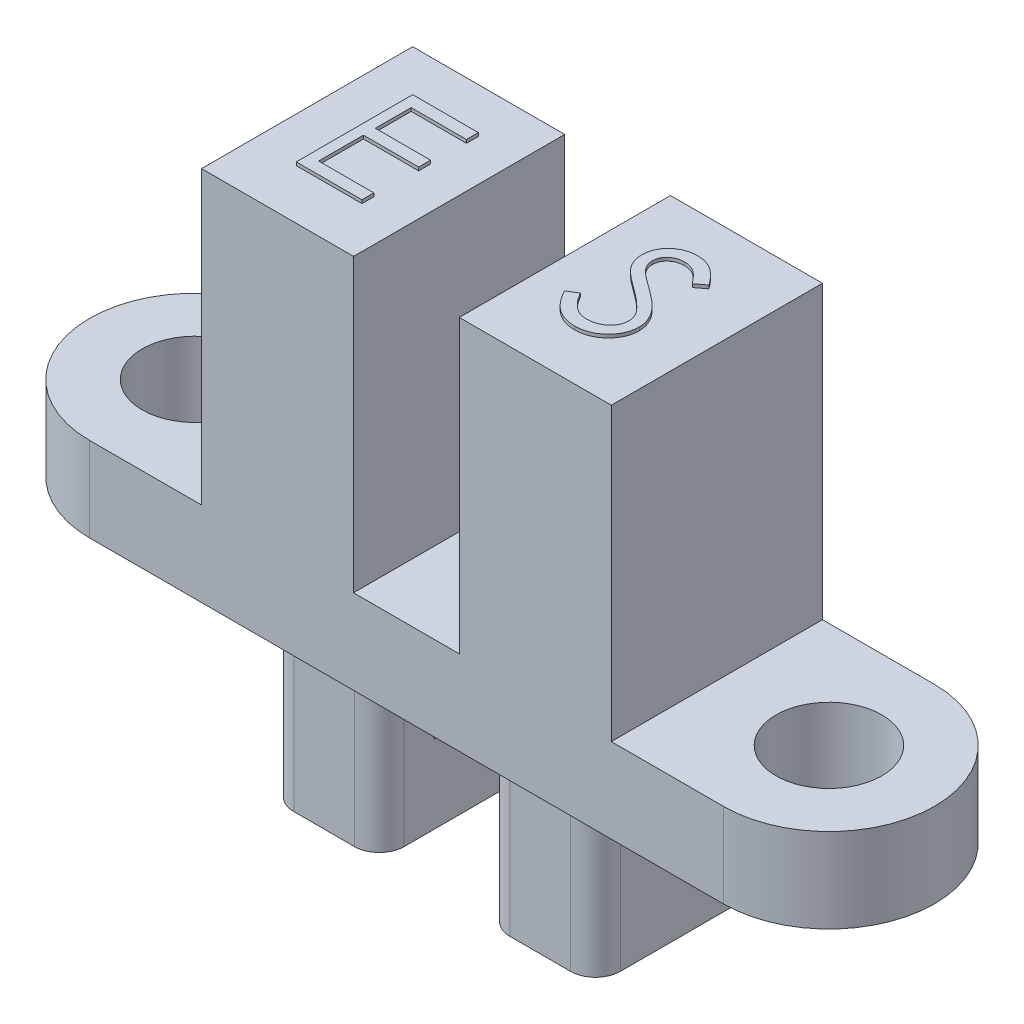
SolidWorks part; units mm, degrees
ref_plane "Front Plane" through (0, 0, 0) normal (0, 0, 1) x (1, 0, 0)
ref_plane "Top Plane" through (0, 0, 0) normal (0, 1, 0) x (1, 0, 0)
ref_plane "Right Plane" through (0, 0, 0) normal (1, 0, 0) x (0, 0, -1)
sketch "Sketch1" plane through (0, 0, 0) normal (0, 1, 0) x (1, 0, 0)
  line L0 (0, 6.2271) -> (0, -7.4076) construction
  line L1 (-9.2668, 0) -> (10.8605, 0) construction
  line L2 (9.53, 3.1745) -> (-9.53, 3.1745)
  line L3 (9.53, -3.1745) -> (-9.53, -3.1745)
  circle A0 centre (-9.53, 0) radius 1.59
  arc A1 (-9.53, 3.1745) -> (-9.53, -3.1745) centre (-9.53, 0) ccw
  circle A2 centre (9.53, 0) radius 1.59
  arc A3 (9.53, 3.1745) -> (9.53, -3.1745) centre (9.53, 0) cw
  point P8 (0, -3.1745)
  point P12 (0, 0)
  point P16 (0, 3.1745)
  dimension "D1" = 3.18
  dimension "D2" = 9.53
  dimension "D3" = 6.349
extrude "Boss-Extrude1" add sketch "Sketch1" along normal blind 2.54
sketch "Sketch2" plane through (0, 2.54, 0) normal (0, 1, 0) x (1, 0, 0)
  line L0 (0, 3.1745) -> (0, -3.1745) construction
  line L1 (9.53, 3.1745) -> (-9.53, 3.1745) construction
  line L2 (-9.53, -3.1745) -> (9.53, -3.1745) construction
  line L3 (-1.59, 3.1745) -> (-1.59, -3.1745)
  line L4 (-6.16, 3.1745) -> (-6.16, -3.1745)
  line L5 (-6.16, 3.1745) -> (-1.59, 3.1745)
  line L6 (-6.16, -3.1745) -> (-1.59, -3.1745)
  line L7 (6.16, 3.1745) -> (6.16, -3.1745)
  line L8 (6.16, 3.1745) -> (1.59, 3.1745)
  line L9 (1.59, 3.1745) -> (1.59, -3.1745)
  line L10 (6.16, -3.1745) -> (1.59, -3.1745)
  dimension "D1" = 3.18
  dimension "D2" = 6.16
extrude "Boss-Extrude2" add sketch "Sketch2" along normal blind 8.76
sketch "Sketch3" plane through (0, 0, 0) normal (0, -1, 0) x (1, 0, 0)
  line L0 (0, 3.1745) -> (0, -3.1745) construction
  line L1 (-9.53, 3.1745) -> (9.53, 3.1745) construction
  line L2 (9.53, -3.1745) -> (-9.53, -3.1745) construction
  line L3 (-5.2064, 0) -> (6.1252, 0) construction
  line L4 (4.91, 2.4) -> (1.59, 2.4)
  line L5 (-4.91, -2.4) -> (-1.59, -2.4)
  line L6 (-4.91, -2.4) -> (-4.91, 2.4)
  line L7 (-4.91, 2.4) -> (-1.59, 2.4)
  line L8 (-1.59, -2.4) -> (-1.59, 2.4)
  line L9 (-4.91, -2.4) -> (-1.59, 2.4) construction
  line L10 (-4.91, 2.4) -> (-1.59, -2.4) construction
  line L11 (1.59, -2.4) -> (1.59, 2.4)
  line L12 (4.91, -2.4) -> (1.59, -2.4)
  line L13 (4.91, -2.4) -> (4.91, 2.4)
  point P7 (-3.25, 0)
  dimension "D1" = 3.18
  dimension "D2" = 4.8
  dimension "D3" = 3.32
extrude "Boss-Extrude3" add sketch "Sketch3" along normal blind 4.83
sketch "Sketch6" plane through (0, 0, 0) normal (0, 0, 1) x (1, 0, 0)
  line L0 (1.59, -4.83) -> (1.59, 0) construction
  line L1 (-1.59, -4.83) -> (-1.59, 0) construction
  line L2 (9.53, 0) -> (-9.53, 0) construction
  line L3 (-1.59, -2.5) -> (-1.59, 0)
  line L4 (-1.59, 0) -> (1.59, 0)
  line L5 (1.59, 0) -> (1.59, -2.5)
  arc A0 (1.59, -2.5) -> (-1.59, -2.5) centre (0, -2.5) ccw
  dimension "D1" = 2.5
extrude "Boss-Extrude5" add sketch "Sketch6" along normal blind 0.75 and the other way blind 0.75
sketch "Sketch7" plane through (0, 0, 0) normal (0, -1, 0) x (1, 0, 0)
  line L0 (4.91, 2.4) -> (1.59, 2.4) construction
  line L1 (5.41, -2.9) -> (-5.41, -2.9)
  line L2 (5.41, -2.9) -> (5.41, 2.9)
  line L3 (5.41, 2.9) -> (-5.41, 2.9)
  line L4 (-5.41, -2.9) -> (-5.41, 2.9)
  line L5 (5.41, -2.9) -> (-5.41, 2.9) construction
  line L6 (5.41, 2.9) -> (-5.41, -2.9) construction
  line L7 (4.91, -2.4) -> (4.91, 2.4) construction
  line L9 (-5.31, -2.8) -> (5.31, -2.8)
  line L10 (-5.31, -2.8) -> (-5.31, 2.8)
  line L11 (-5.31, 2.8) -> (5.31, 2.8)
  line L12 (5.31, -2.8) -> (5.31, 2.8)
  line L13 (-5.31, -2.8) -> (5.31, 2.8) construction
  line L14 (-5.31, 2.8) -> (5.31, -2.8) construction
  point P0 (0, 0)
  point P10 (0, 0)
  dimension "D1" = 0.5
  dimension "D2" = 0.5
  dimension "D3" = 0.1
  dimension "D4" = 0.1
extrude "Cut-Extrude1" cut sketch "Sketch7" against normal blind 0.2
fillet "Fillet1" radius 0.75 8 edges at (4.91, -2.415, -2.4) (1.59, -2.415, 2.4) (1.59, -2.415, -2.4) (4.91, -2.415, 2.4) (-1.59, -2.415, 2.4) (-1.59, -2.415, -2.4) (-4.91, -2.415, -2.4) (-4.91, -2.415, 2.4)
sketch "Sketch8" plane through (0, 11.3, 0) normal (0, 1, 0) x (1, 0, 0)
  line L0 (-6.16, -3.1745) -> (-1.59, -3.1745) construction
  line L1 (-6.16, 3.1745) -> (-6.16, -3.1745) construction
  line L2 (1.59, 3.1745) -> (1.59, -3.1745) construction
  text T0 "E" font "Century Gothic" height 3.5
  text T1 "S"
  point P2 (0, 0)
  point P7 (0, 0)
  point P8 (-5.26, -1.6745)
  point P9 (0, 0)
  dimension "D1" = 1.5
  dimension "D2" = 0.9
  dimension "D3" = 0.9
extrude "Boss-Extrude6" add sketch "Sketch8" along normal blind 0.1
